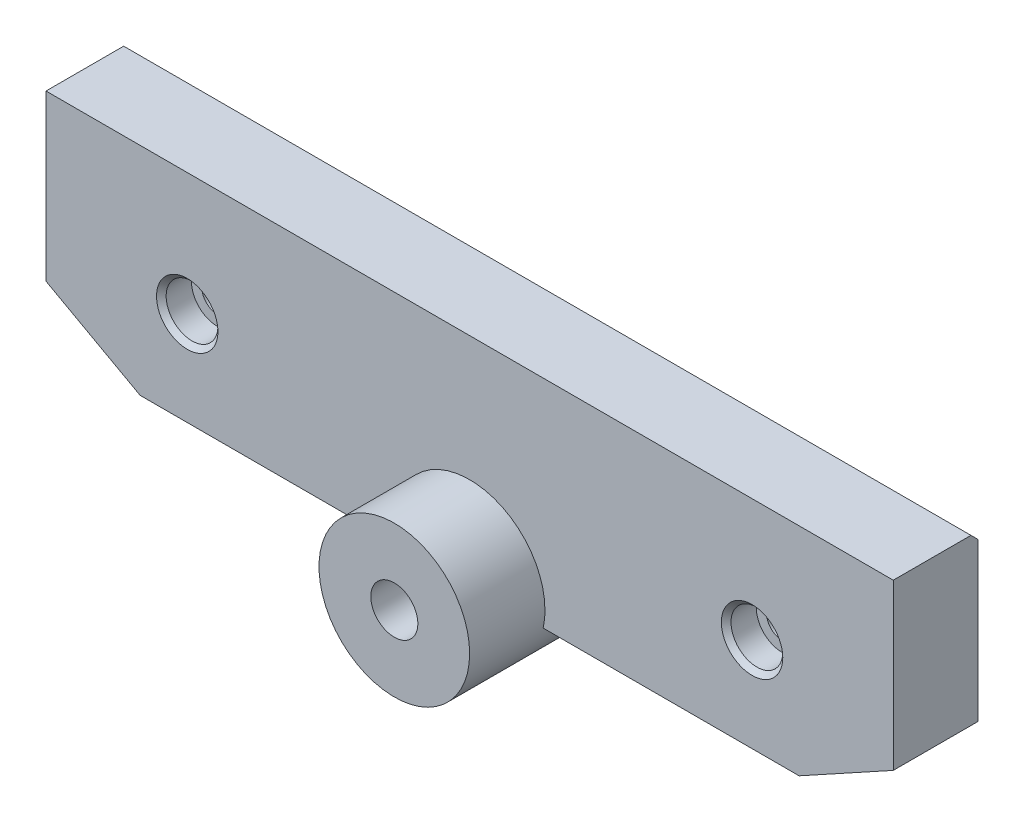
SolidWorks part; units mm, degrees
ref_plane "Front Plane" through (0, 0, 0) normal (0, 0, 1) x (1, 0, 0)
ref_plane "Top Plane" through (0, 0, 0) normal (0, 1, 0) x (1, 0, 0)
ref_plane "Right Plane" through (0, 0, 0) normal (1, 0, 0) x (0, 0, -1)
sketch "Sketch1" plane through (0, 0, 0) normal (0, 0, 1) x (1, 0, 0)
  line L1 (-90, -23) -> (90, -23)
  line L2 (-90, -23) -> (-90, 23)
  line L3 (-90, 23) -> (90, 23)
  line L4 (90, -23) -> (90, 23)
  line L5 (-90, -23) -> (90, 23) construction
  line L6 (-90, 23) -> (90, -23) construction
  point P0 (0, 0)
  dimension "D1" = 180
  dimension "D2" = 46
extrude "Boss-Extrude1" add sketch "Sketch1" along normal blind 18
sketch "Sketch2" plane through (0, 0, 18) normal (0, 0, 1) x (1, 0, 0)
  line L0 (-90, -12) -> (-70, -23)
  line L1 (-90, 23) -> (-90, -23) construction
  line L2 (-90, -23) -> (90, -23) construction
  dimension "D1" = 11
  dimension "D2" = 20
extrude "Cut-Extrude1" cut sketch "Sketch2" against normal blind 18 and the other way through all flip side to cut
sketch "Sketch3" plane through (0, 0, 18) normal (0, 0, 1) x (1, 0, 0)
  line L0 (90, -12) -> (70, -23)
  line L1 (90, -23) -> (90, 23) construction
  line L2 (-70, -23) -> (90, -23) construction
  dimension "D1" = 11
  dimension "D2" = 20
extrude "Cut-Extrude2" cut sketch "Sketch3" against normal blind 18 and the other way through all
sketch "Sketch4" plane through (0, 0, 18) normal (0, 0, 1) x (1, 0, 0)
  line L0 (90, 23) -> (-90, 23) construction
  circle A0 centre (0, -19.5) radius 16
  dimension "D2" = 32
  dimension "D1" = 42.5
extrude "Boss-Extrude2" add sketch "Sketch4" against normal blind 18
sketch "Sketch5" plane through (0, 0, 18) normal (0, 0, 1) x (1, 0, 0)
  line L0 (90, 23) -> (-90, 23) construction
  circle A0 centre (0, -19.5) radius 16
  dimension "D2" = 32
  dimension "D1" = 42.5
extrude "Boss-Extrude3" add sketch "Sketch5" along normal blind 16
sketch "Sketch6" plane through (0, 0, 34) normal (0, 0, 1) x (1, 0, 0)
  line L0 (90, 23) -> (-90, 23) construction
  circle A0 centre (0, -19.5) radius 5
  dimension "D2" = 10
  dimension "D1" = 42.5
extrude "Cut-Extrude3" cut sketch "Sketch6" against normal through all
hole_wizard "CBORE for M6 Hex Socket Head Cap Screw1" positions "3DSketch2" profile "Sketch8" counterbore size "M6" standard "ISO" end condition through all
sketch3d "3DSketch2"
  line L0 (-90, 23, 18) -> (-90, -12, 18) construction
  line L1 (90, -12, 18) -> (90, 23, 18) construction
  line L2 (90, 23, 18) -> (-90, 23, 18) construction
  point P0 (-60, -3, 18)
  point P3 (60, -3, 18)
  dimension "D1" = 30
  dimension "D2" = 30
  dimension "D3" = 26
  dimension "D4" = 26
sketch "Sketch8" plane through (-60, -3, 18) normal (1, 0, 0) x (0, -1, 0)
  line L0 (0, 0) -> (0, 18)
  line L1 (0, 18) -> (3.3, 18)
  line L3 (3.3, 18) -> (3.3, 6.4)
  line L4 (5.5, 6.4) -> (3.3, 6.4)
  line L5 (5.5, 6.4) -> (5.5, 1.025)
  line L6 (5.5, 1.025) -> (6.525, 0)
  line L7 (6.525, 0) -> (0, 0)
  line L8 (-5.5, 1.025) -> (-6.525, 0) construction
  line L11 (0, -6.35) -> (0, 107.95) construction
  dimension "Thru Hole Dia." = 6.6
  dimension "Thru Hole Depth" = 18
  dimension "C'Bore Dia." = 11
  dimension "C'Bore Depth" = 6.4
  dimension "Near C'Sink Dia." = 13.05
  dimension "Near C'Sink Angle" = 90
chamfer "Chamfer1" distance 1.5 angle 45 1 edges at (0, 23, 0)
